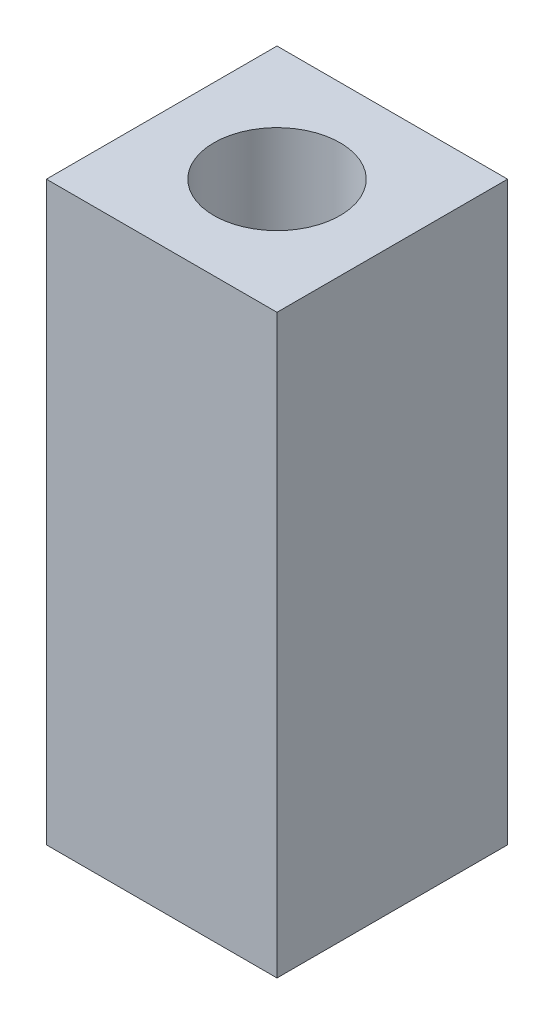
SolidWorks part; units mm, degrees
material "氧化铝"
ref_plane "前视基准面" through (0, 0, 0) normal (0, 0, 1) x (1, 0, 0)
ref_plane "上视基准面" through (0, 0, 0) normal (0, 1, 0) x (1, 0, 0)
ref_plane "右视基准面" through (0, 0, 0) normal (1, 0, 0) x (0, 0, -1)
sketch "草图1" plane through (0, 0, 0) normal (0, 1, 0) x (1, 0, 0)
  line L1 (-25, -25) -> (25, -25)
  line L2 (-25, -25) -> (-25, 25)
  line L3 (-25, 25) -> (25, 25)
  line L4 (25, -25) -> (25, 25)
  line L5 (-25, -25) -> (25, 25) construction
  line L6 (-25, 25) -> (25, -25) construction
  point P0 (0, 0)
  dimension "D1" = 50
  dimension "D2" = 50
extrude "凸台-拉伸1" add sketch "草图1" along normal blind 125
sketch "草图3" plane through (0, 0, 0) normal (0, 0, 1) x (1, 0, 0)
  line L0 (0, 125) -> (0, 25)
  line L1 (-25, 125) -> (25, 125) construction
  line L2 (0, 25) -> (5, 25)
  line L3 (5, 25) -> (13.6824, 74.2404)
  line L4 (13.6824, 74.2404) -> (13.6824, 125)
  line L5 (13.6824, 125) -> (0, 125)
  dimension "D1" = 50
  dimension "D2" = 100
  dimension "D3" = 5
  dimension "D4" = 10
revolve "切除-旋转1" cut sketch "草图3" angle 360 about L0
sketch "草图4" plane through (-25, 0, 0) normal (-1, 0, 0) x (0, 0, 1)
  line L0 (-25, 125) -> (-25, 0) construction
  line L1 (-25, 125) -> (25, 125) construction
  circle A0 centre (0, 86.74) radius 2.5
  dimension "D1" = 25
  dimension "D2" = 38.26
extrude "切除-拉伸1" cut sketch "草图4" against normal up to next
